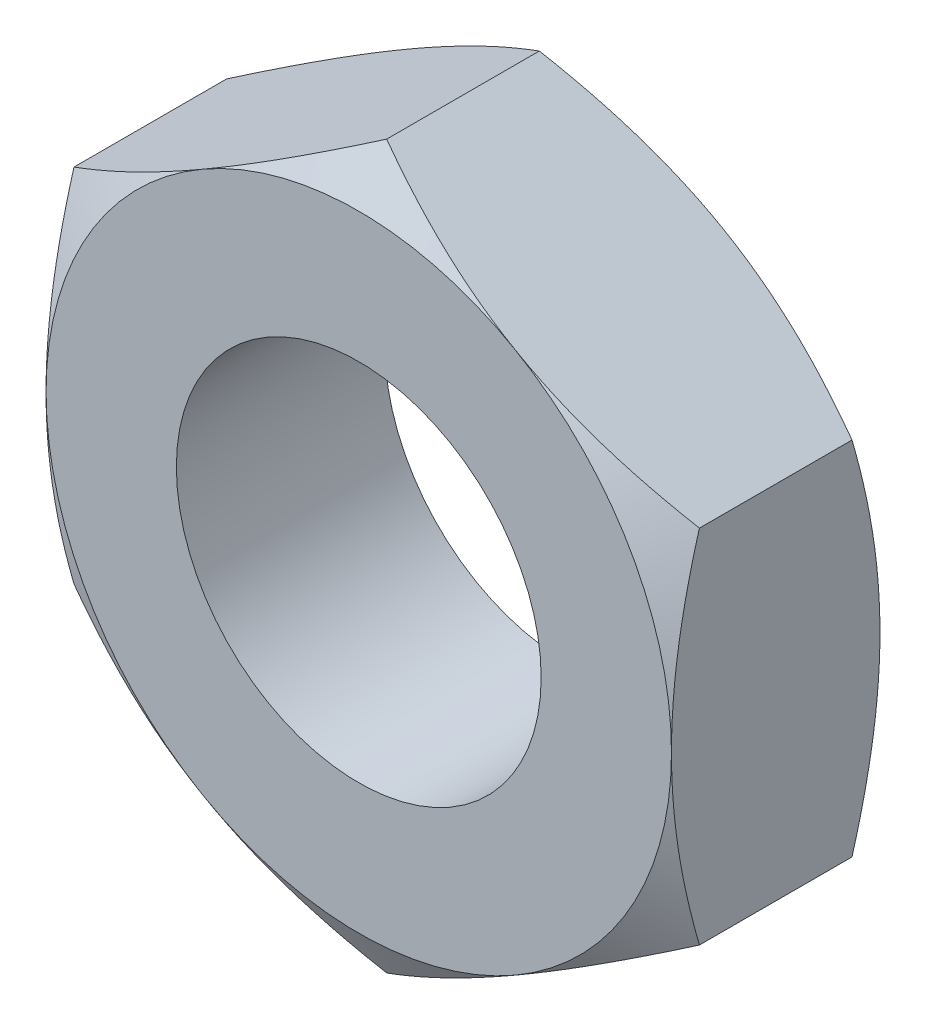
SolidWorks part; units mm, degrees
ref_plane "Ebene1" through (0, 0, 0) normal (0, 0, 1) x (1, 0, 0)
ref_plane "Ebene2" through (0, 0, 0) normal (0, 1, 0) x (1, 0, 0)
ref_plane "Ebene3" through (0, 0, 0) normal (1, 0, 0) x (0, 0, -1)
sketch "Skizze1" plane through (0, 0, 0) normal (0, 0, 1) x (1, 0, 0)
  line L1 (0, -13.8564) -> (12, -6.9282)
  line L2 (12, -6.9282) -> (12, 6.9282)
  line L3 (12, 6.9282) -> (0, 13.8564)
  line L4 (0, 13.8564) -> (-12, 6.9282)
  line L5 (-12, 6.9282) -> (-12, -6.9282)
  line L6 (-12, -6.9282) -> (0, -13.8564)
  circle A0 centre (0, 0) radius 12 construction
extrude "Basis-Linear austragen" add sketch "Skizze1" along normal blind 8
sketch "Skizze2" plane through (0, 0, 0) normal (1, 0, 0) x (0, 0, -1)
  line L0 (0.9211, 0) -> (-5.9405, 0) construction
  line L2 (3.5095, 0) -> (-3.5095, 0) construction
  line L3 (-8, 12) -> (-6.9282, 13.8564)
  line L4 (-8, 6.9282) -> (-8, 13.8564) construction
  line L5 (-8, 13.8564) -> (0, 13.8564) construction
  line L6 (-6.9282, 13.8564) -> (-1.0718, 13.8564)
  line L7 (-1.0718, 13.8564) -> (0, 12)
  line L8 (0, 6.4555) -> (0, -6.4555) construction
  line L9 (0, 12) -> (0, 14.8564)
  line L10 (0, 14.8564) -> (-8, 14.8564)
  line L11 (-8, 14.8564) -> (-8, 12)
  dimension "D1" = 30
  dimension "D2" = 30
  dimension "D4" = 1
revolve "Schnitt-Rotation1" cut sketch "Skizze2" angle 360 about L0
hole_wizard "Bohrung1" positions "Skizze4" profile "Skizze3" tap size "M5x0.8" standard "Ansi Metrisch" end condition through all
sketch "Skizze4" plane through (0, 0, 8) normal (0, 0, 1) x (1, 0, 0)
  point P0 (0, 0)
sketch "Skizze3" plane through (0, 0, 8) normal (1, 0, 0) x (0, -1, 0)
  line L0 (0, 0) -> (0, 8)
  line L1 (0, 8) -> (7, 8)
  line L2 (7, 8) -> (7, 0)
  line L5 (7, 0) -> (0, 0)
  line L11 (0, -6.35) -> (0, 107.95) construction
  dimension "Bohrerdurchmesser" = 14
  dimension "Bohrungstiefe" = 8
